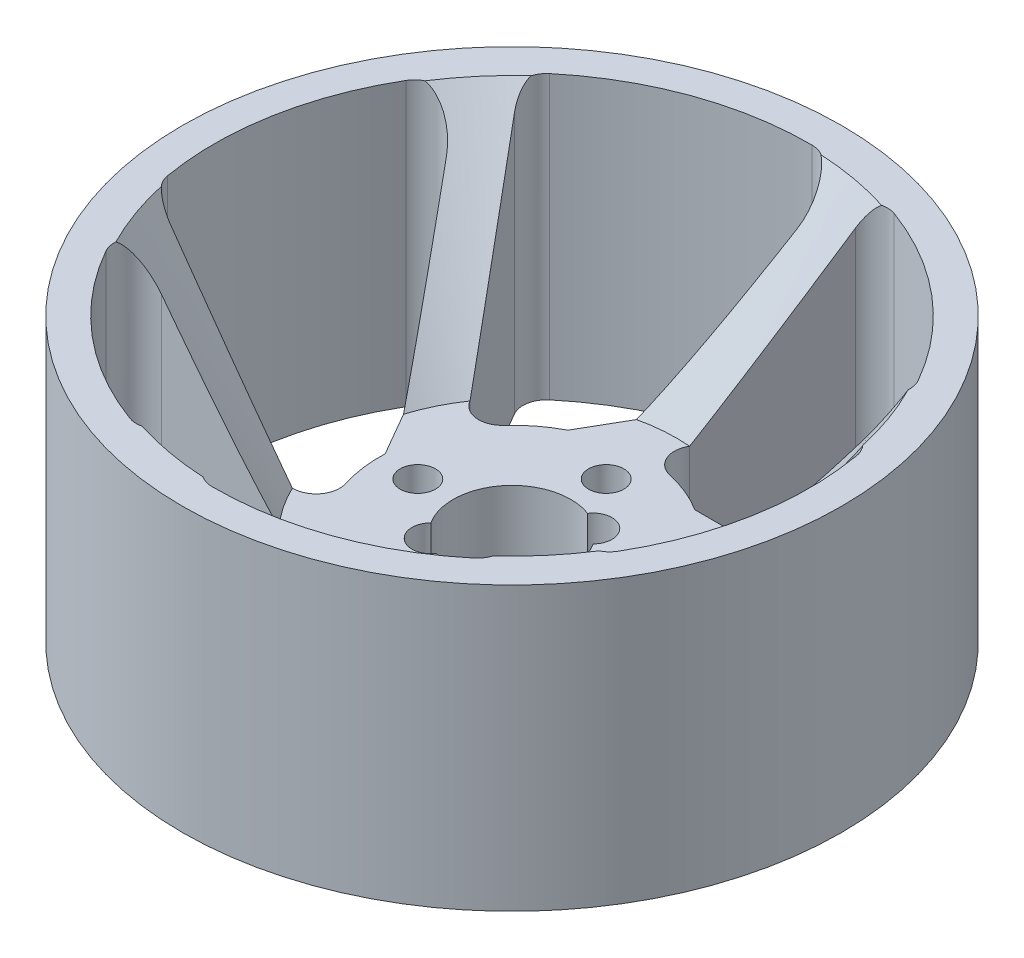
SolidWorks part; units mm, degrees
ref_plane "Front Plane" through (0, 0, 0) normal (0, 0, 1) x (1, 0, 0)
ref_plane "Top Plane" through (0, 0, 0) normal (0, 1, 0) x (1, 0, 0)
ref_plane "Right Plane" through (0, 0, 0) normal (1, 0, 0) x (0, 0, -1)
sketch "Sketch1" plane through (0, 0, 0) normal (0, 1, 0) x (1, 0, 0)
  circle A0 centre (0, 0) radius 28
  dimension "D1" = 56
extrude "Boss-Extrude1" add sketch "Sketch1" along normal blind 24
sketch "Sketch3" plane through (0, 0, 0) normal (0, 1, 0) x (1, 0, 0)
  line L0 (5.4848, 9.5) -> (23.4487, 9.5)
  line L1 (3.4641, 6) -> (-3.4641, 6) construction
  line L2 (-3.4641, 6) -> (-6.9282, 0) construction
  line L4 (-6.9282, 0) -> (-3.4641, -6) construction
  line L5 (-3.4641, -6) -> (3.4641, -6) construction
  line L6 (3.4641, -6) -> (6.9282, 0) construction
  line L7 (6.9282, 0) -> (3.4641, 6) construction
  line L9 (-6.9282, 0) -> (7.093, 24.2854)
  line L11 (5.4848, 9.5) -> (-5.4848, 9.5) construction
  line L12 (-5.4848, 9.5) -> (-10.9697, 0) construction
  line L13 (-10.9697, 0) -> (-5.4848, -9.5) construction
  line L14 (-5.4848, -9.5) -> (5.4848, -9.5) construction
  line L15 (5.4848, -9.5) -> (10.9697, 0) construction
  line L16 (10.9697, 0) -> (5.4848, 9.5) construction
  circle A0 centre (0, 0) radius 25.3
  circle A10 centre (0, 0) radius 6 construction
  circle A11 centre (0, 0) radius 9.5 construction
  circle A12 centre (0, 0) radius 28 construction
  circle A22 centre (0, 0) radius 28 construction
  arc A23 (8.7007, 23.7568) -> (6.2809, 22.8788) centre (8.0129, 21.8788) ccw
  arc A28 (20.2643, 9.5) -> (22.0037, 12.4871) centre (20.2643, 11.5) ccw
  circle A29 centre (0, 0) radius 11.25
  arc A30 (1.1198, 13.9395) -> (2.4213, 10.9863) centre (2.8518, 12.9395) ccw
  point P6 (10.9697, 20.6093)
  dimension "D2" = 3.5
  dimension "D3" = 12
  dimension "D4" = 2.7
  dimension "D5" = 4
  dimension "D6" = 22.5
sketch "Sketch6" plane through (0, 0, 0) normal (0, 1, 0) x (1, 0, 0)
  circle A0 centre (0, 0) radius 1.9
  dimension "D1" = 3.8
extrude "Cut-Extrude6" cut sketch "Sketch6" along normal up to surface (24 mm away) up to face at (0, 24, 28)
ref_plane "Plane1" through (0, 12, 0) normal (0, 1, 0) x (1, 0, 0)
extrude "Cut-Extrude7" cut sketch "Sketch3" along normal up to surface (24 mm away)
pattern_circular "CirPattern1" count 6 over 360 about axis through (0, 0, 0) along (0, 1, 0) of "Cut-Extrude7"
sketch "Sketch8" plane through (0, 12, 0) normal (0, 1, 0) x (1, 0, 0)
  line L0 (0, 0) -> (0, -28) construction
  line L5 (-4.4539, -25.6157) -> (4.4539, -25.6157)
  line L6 (-2.5, -29) -> (2.5, -29)
  line L7 (4.4539, -25.6157) -> (2.5, -29)
  line L8 (-4.4539, -25.6157) -> (-2.5, -29)
  circle A7 centre (0, 0) radius 26 construction
  circle A8 centre (0, 0) radius 28 construction
  point P10 (0, -25.6157)
  point P13 (0, -29)
  dimension "D1" = 2
  dimension "D2" = 1
  dimension "D3" = 60
  dimension "D4" = 5
sketch "Sketch13" plane through (0, 24, 0) normal (0, 1, 0) x (0.9417, 0, -0.3365)
  line L0 (0, 0) -> (0, -28) construction
  line L5 (-4.4539, -25.6157) -> (4.4539, -25.6157)
  line L6 (-2.5, -29) -> (2.5, -29)
  line L7 (4.4539, -25.6157) -> (2.5, -29)
  line L8 (-4.4539, -25.6157) -> (-2.5, -29)
  circle A7 centre (0, 0) radius 26 construction
  point P10 (0, -25.6157)
  point P13 (0, -29)
loft "Cut-Loft6" [suppressed] cut profiles "Sketch13", "Sketch8"
mirror "Mirror10" [suppressed] about plane through (0, 12, 0) normal (0, 1, 0)
pattern_circular "CirPattern6" [suppressed] count 6 over 360
sketch "Sketch14" plane through (0, 0, 0) normal (0, 0, 1) x (1, 0, 0)
  line L1 (28, 0) -> (28, 24) construction
  line L2 (25.5, 13) -> (25.5, 12)
  line L3 (30.8, 12) -> (-30.8, 12) construction
  line L4 (25.5, 12) -> (28, 12)
  line L5 (25.5, 13) -> (28, 14)
  line L6 (28, 14) -> (28, 12)
  dimension "D1" = 2.5
  dimension "D2" = 2
  dimension "D3" = 1
revolve "Revolve1" add sketch "Sketch14" angle 360 about axis through (0, 24, 0) along (0, -1, 0)
mirror "Mirror11" about plane through (0, 12, 0) normal (0, 1, 0) of "Revolve1"
sketch "Sketch15" plane through (0, 0, 0) normal (0, 0, 1) x (1, 0, 0)
  line L0 (5, 8) -> (5, 0)
  line L1 (5, 8) -> (14, 8)
  line L2 (-28, 0) -> (28, 0) construction
  line L3 (14, 8) -> (25, 24)
  line L4 (28, 24) -> (-28, 24) construction
  line L5 (25, 24) -> (0, 24)
  line L6 (0, 0) -> (0, 34.2011) construction
  line L7 (0, 24) -> (0, 0) construction
  line L8 (5, 0) -> (0, 0)
  line L9 (0, 8) -> (0, 0)
  line L10 (-1.1198, 24) -> (-6.2809, 24) construction
  line L14 (0, 8) -> (0, 0) construction
  line L16 (0, 24) -> (0, 0) construction
  line L19 (0, 8) -> (0, 24)
  dimension "D1" = 16
  dimension "D2" = 25
  dimension "D3" = 14
  dimension "D4" = 5
revolve "Cut-Revolve5" cut sketch "Sketch15" angle 360 about L14
sketch "Sketch16" plane through (0, 0, 0) normal (0, 1, 0) x (1, 0, 0)
  line L1 (0, 6.9398) -> (-6.01, 3.4699)
  line L2 (-6.01, 3.4699) -> (-6.01, -3.4699)
  line L3 (-6.01, -3.4699) -> (0, -6.9398)
  line L4 (0, -6.9398) -> (6.01, -3.4699)
  line L5 (6.01, -3.4699) -> (6.01, 3.4699)
  line L6 (6.01, 3.4699) -> (0, 6.9398)
  circle A0 centre (0, 0) radius 6.01 construction
  dimension "D1" = 12.02
extrude "Cut-Extrude8" [suppressed] cut sketch "Sketch16" along normal blind 9
sketch "Sketch17" plane through (0, 0, 0) normal (0, 1, 0) x (1, 0, 0)
  circle A0 centre (0, 0) radius 8 construction
  circle A1 centre (0, 8) radius 1.5
  circle A2 centre (8, 0) radius 1.5
  circle A3 centre (0, -8) radius 1.5
  circle A4 centre (-8, 0) radius 1.5
  point P14 (0, 0)
  dimension "D1" = 16
  dimension "D2" = 3
  dimension "D3" = 4
extrude "Cut-Extrude9" cut sketch "Sketch17" along normal up to surface (8 mm away) up to face at (0, 8, 5)
sketch "Sketch18" plane through (0, 0, 0) normal (0, 1, 0) x (1, 0, 0)
  line L0 (-3.0808, -3.8007) -> (3.0808, 3.8007) construction
  line L1 (-4.093, -5.0495) -> (4.093, 5.0495) construction
  circle A1 centre (3.0808, 3.8007) radius 1.6075
  circle A2 centre (-3.0808, -3.8007) radius 1.6075
  circle A3 centre (0, 0) radius 5 construction
  point P3 (0, 0)
  point P5 (1.74, 4.6875)
  point P6 (4.2259, 2.6725)
  point P8 (0, 0)
  point P11 (0, 0)
  point P14 (0, 0)
  point P15 (4.2259, 5.0495)
  dimension "D2" = 3.2
  dimension "D1" = 13
extrude "Cut-Extrude10" cut sketch "Sketch18" against normal up to surface (12 mm away)
